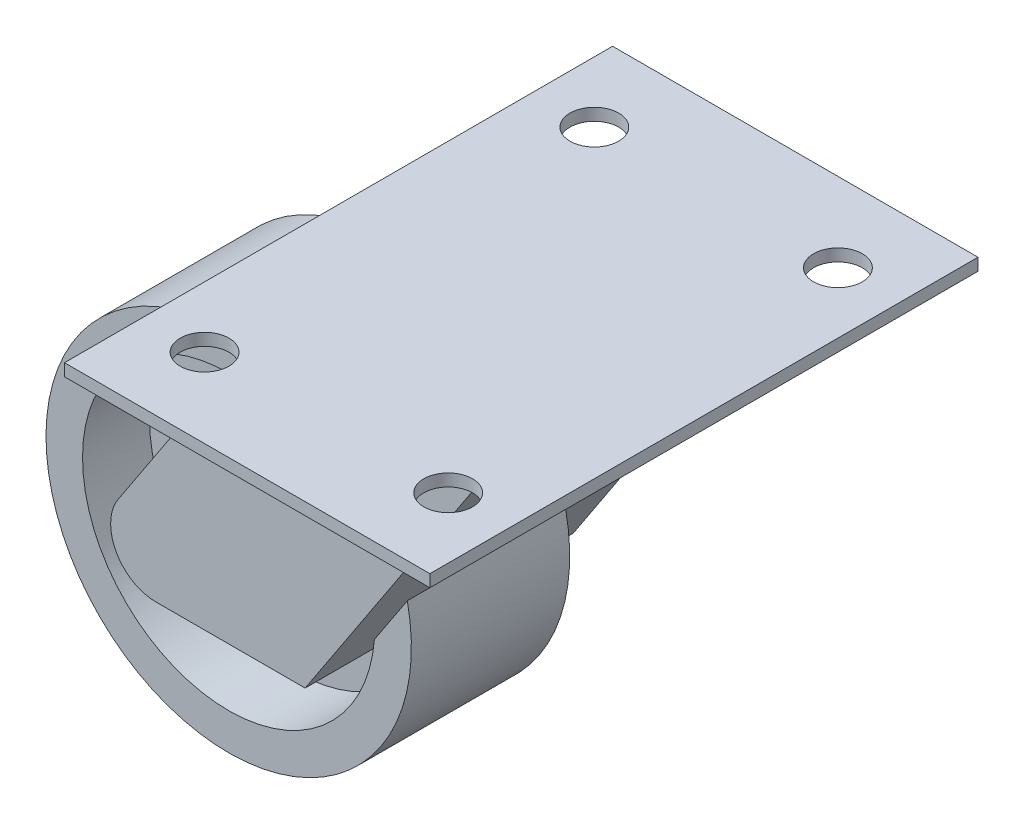
SolidWorks part; units mm, degrees
ref_plane "Alzado" through (0, 0, 0) normal (0, 0, 1) x (1, 0, 0)
ref_plane "Planta" through (0, 0, 0) normal (0, 1, 0) x (1, 0, 0)
ref_plane "Vista lateral" through (0, 0, 0) normal (1, 0, 0) x (0, 0, -1)
sketch "Croquis1" plane through (0, 0, 0) normal (0, 0, 1) x (1, 0, 0)
  circle A0 centre (0, 0) radius 15
  dimension "D1" = 30
extrude "Extruir-Lámina1" add sketch "Croquis1" along normal mid plane 13 thin thin type one direction reverse wall 3
sketch "Croquis2" plane through (0, 0, 0) normal (0, 0, 1) x (1, 0, 0)
  circle A0 centre (0, 0) radius 5
  dimension "D1" = 10
extrude "Saliente-Extruir1" add sketch "Croquis2" along normal mid plane 13 separate body
sketch "Croquis3" plane through (0, 0, 0) normal (0, 0, 1) x (1, 0, 0)
  circle A0 centre (0, 0) radius 12.5
  dimension "D1" = 25
extrude "Saliente-Extruir2" add sketch "Croquis3" along normal mid plane 2 contours A0
sketch "Croquis4" plane through (0, 0, 0) normal (0, 0, 1) x (1, 0, 0)
  circle A0 centre (0, 0) radius 2
  dimension "D1" = 4
extrude "Saliente-Extruir3" add sketch "Croquis4" along normal mid plane 22
sketch "Croquis6" plane through (0, 0, 11) normal (0, 0, 1) x (1, 0, 0)
  line L4 (0, 0) -> (6.873, 0) construction
  line L9 (-4.5819, 2.978) -> (7.9497, 22)
  line L10 (-1.4926, -2.7567) -> (10.7769, -2.7567)
  line L11 (7.9497, 22) -> (27.0863, 22)
  line L12 (10.7769, -2.7567) -> (27.0863, 22)
  arc A1 (-1.4926, -2.7567) -> (-4.5819, 2.978) centre (-1.4926, 0.9428) cw
  point P3 (12.1182, -5.4803)
  point P5 (25.6389, 19.0282)
extrude "Saliente-Extruir4" add sketch "Croquis6" against normal through all
sketch "Croquis9" plane through (0, 22, 0) normal (0, 1, 0) x (1, 0, 0)
  line L1 (32.5197, -22.5) -> (2.5197, -22.5)
  line L2 (32.5197, -22.5) -> (32.5197, 22.5)
  line L3 (32.5197, 22.5) -> (2.5197, 22.5)
  line L4 (2.5197, -22.5) -> (2.5197, 22.5)
  line L5 (32.5197, -22.5) -> (2.5197, 22.5) construction
  line L6 (32.5197, 22.5) -> (2.5197, -22.5) construction
  line L7 (27.0863, 11) -> (27.0863, -11) construction
  line L8 (17.5197, 0) -> (17.5197, 12.8316) construction
  line L9 (17.5197, 0) -> (30.1488, 0) construction
  circle A0 centre (27.5197, 16) radius 2
  circle A1 centre (7.5197, 16) radius 2
  circle A2 centre (7.5197, -16) radius 2
  circle A3 centre (27.5197, -16) radius 2
  point P0 (17.5197, 0)
  point P19 (0, 0)
  dimension "D3" = 4
  dimension "D1" = 30
  dimension "D2" = 9.5667
  dimension "D4" = 10
  dimension "D5" = 16
  dimension "D6" = 45
extrude "Saliente-Extruir5" add sketch "Croquis9" against normal blind 1
